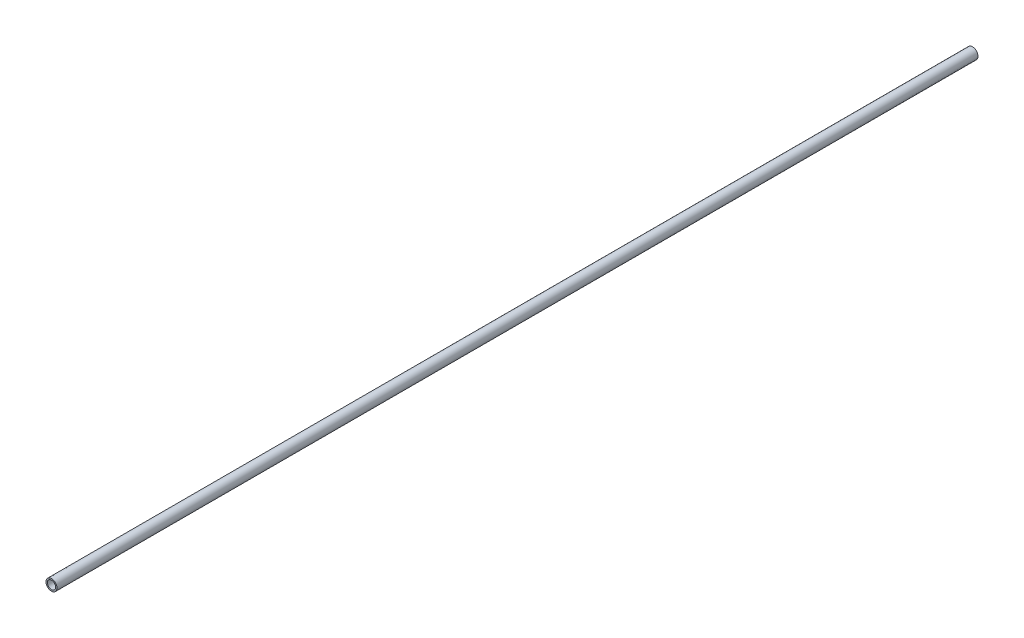
SolidWorks part; units mm, degrees
material "Fr-4"
ref_plane "Front Plane" through (0, 0, 0) normal (0, 0, 1) x (1, 0, 0)
ref_plane "Top Plane" through (0, 0, 0) normal (0, 1, 0) x (1, 0, 0)
ref_plane "Right Plane" through (0, 0, 0) normal (1, 0, 0) x (0, 0, -1)
sketch "Sketch1" plane through (0, 0, 0) normal (0, 0, 1) x (1, 0, 0)
  line L0 (-6.35, 0) -> (6.35, 0) construction
  line L1 (0, -6.35) -> (0, 6.35) construction
  circle A0 centre (0, 0) radius 6.35
  circle A1 centre (0, 0) radius 4.7625
  point P4 (0, 0)
  point P9 (0, 0)
  point P10 (4.7625, 0)
  dimension "ID" = 9.525
  dimension "OD" = 12.7
  dimension "Wall Thickness" = 1.5875
sketch "Sketch2" plane through (0, 0, 0) normal (1, 0, 0) x (0, 0, -1)
  line L0 (533.4, 6.35) -> (-533.4, 6.35) construction
  line L1 (0, 6.35) -> (0, -6.35) construction
  point P3 (-518.795, 6.35)
  point P4 (0, 6.35)
  point P5 (518.795, 6.35)
  dimension "Length" = 1066.8
  dimension "D1" = 14.605
  dimension "D2" = 14.605
sketch "Sketch3" plane through (0, 0, 0) normal (0, 0, 1) x (1, 0, 0)
  line L0 (0, -6.35) -> (0, 6.35) construction
  circle A0 centre (0, 0) radius 6.35
  circle A1 centre (0, 0) radius 4.7625
  circle A2 centre (0, 0) radius 4.7625 construction
extrude "Boss-Extrude1" add sketch "Sketch3" along normal mid plane 1066.8
equation "\"D1@Boss-Extrude1\" = \"Length@Sketch2\""
equation "\"D1@Sketch2\"=\"OD@Sketch1\"*1.15"
equation "\"D2@Sketch2\"=\"D1@Sketch2\""
